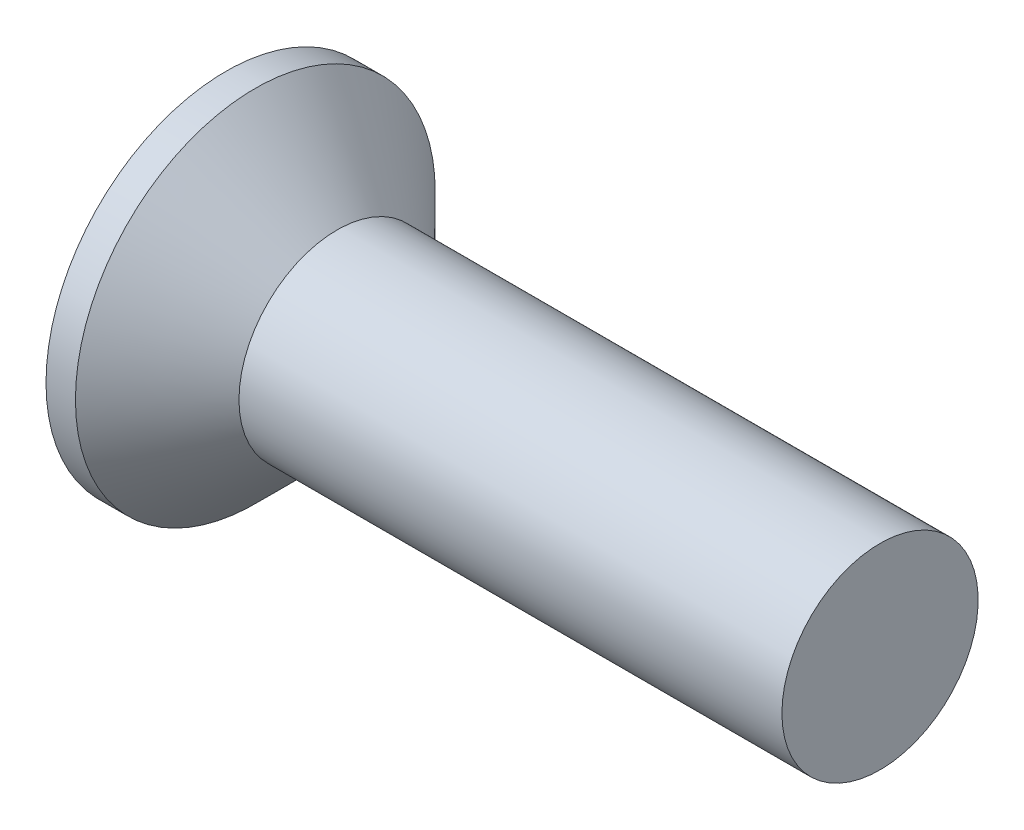
SolidWorks part; units mm, degrees
revolve "Base-Revolve" add sketch "BodySke" angle 360 about L5
sketch "BodySke" plane through (0, 0, 0) normal (0, 0, 1) x (1, 0, 0)
  line L0 (0, 0) -> (0, 2.75)
  line L1 (0, 2.75) -> (0.45, 2.75)
  line L2 (1.7, 1.5) -> (10, 1.5)
  line L3 (10, 1.5) -> (10, 0)
  line L4 (10, 0) -> (0, 0)
  line L5 (-6.35, 0) -> (82.55, 0) construction
  line L6 (1.7, -1.5) -> (10, -1.5) construction
  line L7 (0.45, -2.75) -> (1.7, -1.5) construction
  line L8 (0.45, 2.75) -> (1.7, 1.5)
  line L9 (0, -2.75) -> (0.45, -2.75) construction
  line L10 (2.2, 3.0875) -> (2.2, -6.4375) construction
  line L11 (0, 6.35) -> (0, -3.175) construction
  dimension "Diameter" = 3
  dimension "Length" = 10
  dimension "Head_ht" = 1.7
  dimension "Head_dia" = 5.5
  dimension "Head_ang" = 90
  dimension "D6" = 0.45
  dimension "Advance" = 0.5
  dimension "Thread_nom" = 10
cosmetic thread "ThreadCosmetic" [suppressed] parameters "Thread_length"=7.8, "Thread_minor"=2.439
extrude "Slot" [suppressed] cut sketch "Sketch2" against normal blind 0.9
sketch "Sketch2" plane through (0, 0, 0) normal (-1, 0, 0) x (0, 0, 1)
  line L0 (-2.75, -0.5) -> (2.75, -0.5)
  line L1 (-2.75, -0.5) -> (-2.75, 0.5)
  line L2 (2.75, 0.5) -> (-2.75, 0.5)
  line L3 (2.75, 0.5) -> (2.75, -0.5)
  dimension "Slot_width" = 1
  dimension "D1" = 0.5
  dimension "D2" = 5.5
  dimension "D3" = 2.75
ref_plane "Plane1" through (0, 0, 0) normal (0, 0, 1) x (1, 0, 0)
ref_plane "Plane2" through (0, 0, 0) normal (0, 1, 0) x (1, 0, 0)
ref_plane "Plane3" through (0, 0, 0) normal (1, 0, 0) x (0, 0, -1)
other "Configuration Table"
sketch "Sketch3" plane through (0, 0, 0) normal (-1, 0, 0) x (0, 0, 1)
  line L0 (-0.395, 1.55) -> (0.395, 1.55)
  line L1 (0.395, 1.55) -> (0.395, -1.55)
  line L2 (0.395, -1.55) -> (-0.395, -1.55)
  line L3 (-0.395, -1.55) -> (-0.395, 1.55)
  dimension "Cross_dia" = 3.1
  dimension "Cross_width" = 0.79
  dimension "D1" = 1.55
  dimension "D2" = 0.395
ref_plane "Plane4" through (2.08, 0, 0) normal (-1, 0, 0) x (0, 0, 1)
sketch "Sketch4" plane through (2.08, 0, 0) normal (-1, 0, 0) x (0, 0, 1)
  line L0 (-0.1975, 0.1975) -> (0.1975, 0.1975)
  line L3 (0.1975, 0.1975) -> (0.1975, -0.1975)
  line L4 (0.1975, -0.1975) -> (-0.1975, -0.1975)
  line L5 (-0.1975, -0.1975) -> (-0.1975, 0.1975)
  dimension "D2" = 0.395
  dimension "D1" = 0.395
  dimension "D3" = 0.1975
  dimension "D4" = 0.1975
loft "Cross" cut profiles "Sketch3", "Sketch4"
pattern_circular "CirPattern1" count 2 every 90 about axis through (0, 0, 0) along (1, 0, 0) of "Cross"
sketch "ThdSchSke" plane through (0, 0, 0) normal (0, 0, 1) x (1, 0, 0)
  line L0 (2.2, -1.2195) -> (2.0036, -1.5)
  line L1 (2.2, -1.2195) -> (2.3964, -1.5)
  line L2 (2.3964, -1.5) -> (2.3964, -1.875)
  line L3 (-3.175, 0) -> (5.1513, 0) construction
  line L5 (2.3964, -1.875) -> (2.0036, -1.875)
  line L6 (2.0036, -1.875) -> (2.0036, -1.5)
  line L7 (0, 2.75) -> (0, -2.75) construction
  dimension "Diameter" = 3
  dimension "Thread_minor" = 2.439
  dimension "Start" = 2.2
revolve "ThreadSchematic" [suppressed] cut sketch "ThdSchSke" angle 360 about L3
pattern_linear "ThdSchPat" [suppressed]
equation "\"D1@Sketch3\" = \"Cross_dia@Sketch3\" / 2"
equation "\"D2@Sketch3\" = \"Cross_width@Sketch3\" / 2"
equation "\"D1@Sketch4\" = \"Cross_width@Sketch3\" *.5"
equation "\"D2@Sketch4\" = \"D1@Sketch4\""
equation "\"D4@Sketch4\" = \"D2@Sketch4\" / 2"
equation "\"D3@Sketch4\" = \"D1@Sketch4\" / 2"
equation "\"D1@Sketch2\" = \"Slot_width@Sketch2\" / 2"
equation "\"D2@Sketch2\" = \"Head_dia@BodySke\""
equation "\"D3@Sketch2\" = \"D2@Sketch2\" / 2"
equation "\"Thread_length@ThreadCosmetic\" = ((sgn( (\"Length@BodySke\" - \"Advance@BodySke\" - \"Head_ht@BodySke\" ) - \"Thread_nom@BodySke\" )-1)*( (\"Length@BodySke\" - \"Advance@BodySke\" - \"Head_ht@BodySke\" ) - \"Thread_nom@BodySke\" ))/-2+ \"Thread_nom@BodySke\""
equation "\"Thread_minor@ThdSchSke\" = \"Thread_minor@ThreadCosmetic\""
equation "\"Diameter@ThdSchSke\" = \"Diameter@BodySke\""
equation "\"Overcut@ThdSchSke\" = \"Diameter@BodySke\" * 1.25"
equation "\"Start@ThdSchSke\" = 0.000001 + \"Length@BodySke\" - \"Thread_length@ThreadCosmetic\"  '---Countersunk---"
equation "\"Num_threads@ThdSchPat\" = int( \"Thread_length@ThreadCosmetic\" / \"Advance@BodySke\" + 0.999 )  + 1"
equation "\"Advance@ThdSchPat\" = \"Thread_length@ThreadCosmetic\" /  (\"Num_threads@ThdSchPat\" - 1) 'relax it"
